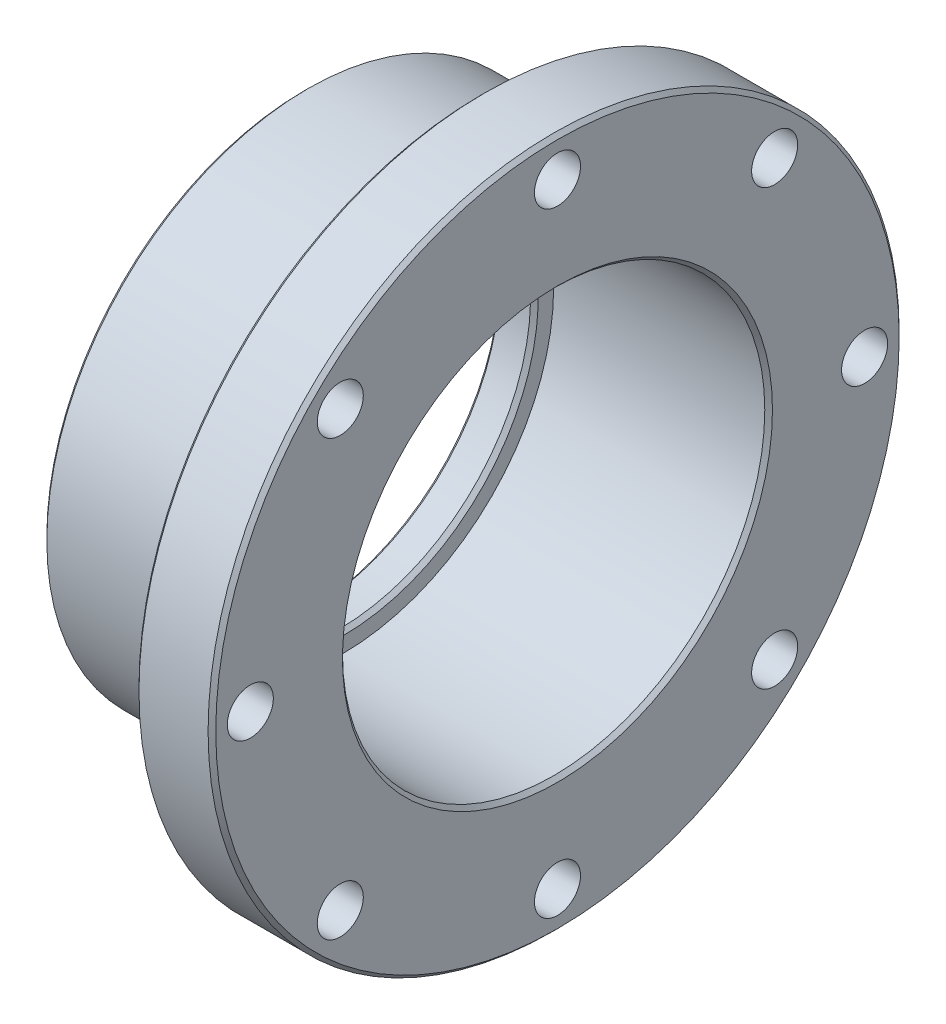
SolidWorks part; units mm, degrees
ref_plane "前视基准面" through (0, 0, 0) normal (0, 0, 1) x (1, 0, 0)
ref_plane "上视基准面" through (0, 0, 0) normal (0, 1, 0) x (1, 0, 0)
ref_plane "右视基准面" through (0, 0, 0) normal (1, 0, 0) x (0, 0, -1)
other "Configuration Table"
sketch "草图1" plane through (0, 0, 0) normal (0, 0, 1) x (1, 0, 0)
  line L0 (0, 0) -> (0, 34)
  line L1 (0, 34) -> (23, 34)
  line L2 (23, 34) -> (23, 45)
  line L3 (23, 45) -> (33, 45)
  line L4 (33, 45) -> (33, 0)
  line L5 (33, 0) -> (0, 0)
  line L6 (0, 0) -> (-22.3549, 0) construction
  dimension "D1" = 68
  dimension "D2" = 90
  dimension "D3" = 23
  dimension "D4" = 33
revolve "旋转1" add sketch "草图1" angle 360 about L6
sketch "草图2" plane through (0, 0, 0) normal (0, 0, 1) x (1, 0, 0)
  line L0 (0, 0) -> (-12.3125, 0) construction
  line L1 (0, 34) -> (0, -34) construction
  line L2 (0, 0) -> (0, 25)
  line L3 (0, 25) -> (5, 25)
  line L4 (5, 25) -> (5, 27.5)
  line L5 (5, 27.5) -> (33, 27.5)
  line L6 (33, -45) -> (33, 45) construction
  line L7 (33, 27.5) -> (33, 0)
  line L8 (33, 0) -> (0, 0)
  dimension "D1" = 50
  dimension "D2" = 55
  dimension "D3" = 28
revolve "切除-旋转1" cut sketch "草图2" angle 360 about L0
sketch "草图3" plane through (23, 0, 0) normal (-1, 0, 0) x (0, 0, 1)
  circle A0 centre (0, 40) radius 3
  circle A1 centre (28.2843, 28.2843) radius 3
  circle A2 centre (40, 0) radius 3
  circle A3 centre (28.2843, -28.2843) radius 3
  circle A4 centre (0, -40) radius 3
  circle A5 centre (-28.2843, -28.2843) radius 3
  circle A6 centre (-40, 0) radius 3
  circle A7 centre (-28.2843, 28.2843) radius 3
  point P20 (0, 0)
  dimension "D1" = 40
  dimension "D2" = 6
  dimension "D3" = 8
extrude "切除-拉伸1" cut sketch "草图3" against normal up to next
chamfer "倒角1" distance 0.5 angle 45 6 edges at (5, 25, 0) (33, 27.5, 0) (33, 0, -45) (23, 0, -45) (0, 0, -34) (0, 25, 0)
